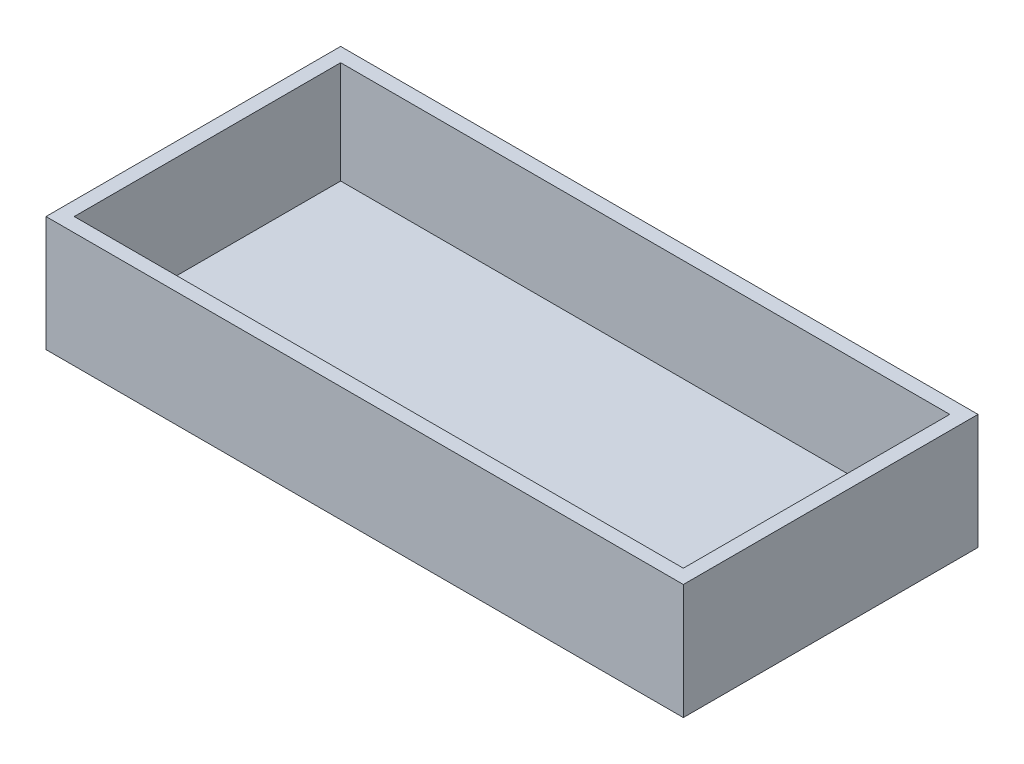
SolidWorks part; units mm, degrees
ref_plane "Front Plane" through (0, 0, 0) normal (0, 0, 1) x (1, 0, 0)
ref_plane "Top Plane" through (0, 0, 0) normal (0, 1, 0) x (1, 0, 0)
ref_plane "Right Plane" through (0, 0, 0) normal (1, 0, 0) x (0, 0, -1)
sketch "Sketch1" plane through (0, 0, 0) normal (0, 1, 0) x (1, 0, 0)
  line L0 (-157.9905, 73.0402) -> (157.9905, 73.0402)
  line L1 (-150.9903, -66.04) -> (150.9903, -66.04)
  line L2 (-150.9903, -66.04) -> (-150.9903, 66.04)
  line L3 (-150.9903, 66.04) -> (150.9903, 66.04)
  line L4 (150.9903, -66.04) -> (150.9903, 66.04)
  line L5 (0, 66.04) -> (0, -66.04) construction
  line L6 (-150.9903, 0) -> (150.9903, 0) construction
  line L7 (157.9905, -73.0402) -> (157.9905, 73.0402)
  line L8 (-157.9905, -73.0402) -> (157.9905, -73.0402)
  line L9 (-157.9905, -73.0402) -> (-157.9905, 73.0402)
  point P0 (0, 0)
  dimension "D1" = 301.9806
  dimension "D2" = 132.08
  dimension "D3" = 7.0002
extrude "Boss-Extrude1" add sketch "Sketch1" along normal blind 50.8
sketch "Sketch3" plane through (0, 0, 0) normal (0, -1, 0) x (1, 0, 0)
  line L4 (-157.9905, 73.0402) -> (-157.9905, -73.0402)
  line L5 (-157.9905, -73.0402) -> (157.9905, -73.0402)
  line L6 (157.9905, -73.0402) -> (157.9905, 73.0402)
  line L7 (157.9905, 73.0402) -> (-157.9905, 73.0402)
  line L8 (-157.9905, 73.0402) -> (-157.9905, -73.0402)
  line L9 (-157.9905, -73.0402) -> (157.9905, -73.0402)
  line L10 (157.9905, -73.0402) -> (157.9905, 73.0402)
  line L11 (157.9905, 73.0402) -> (-157.9905, 73.0402)
  dimension "D1" = 0
extrude "Boss-Extrude2" add sketch "Sketch3" along normal blind 6.35
